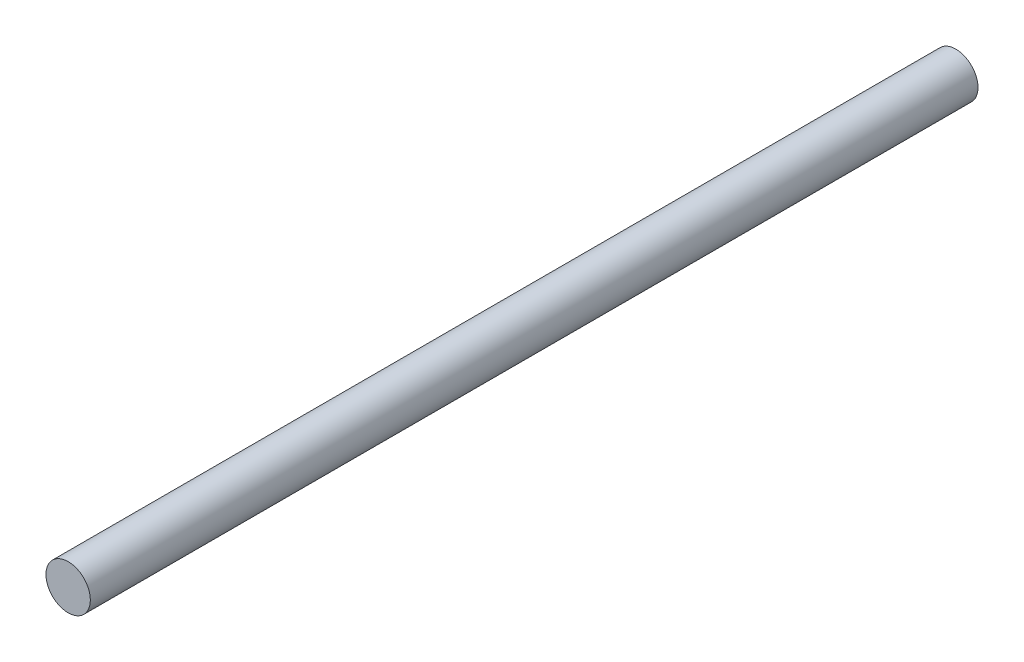
SolidWorks part; units mm, degrees
material "Alliage 1060"
ref_plane "Plan de dessus" through (0, 0, 0) normal (0, 0, 1) x (1, 0, 0)
ref_plane "Plan de droite" through (0, 0, 0) normal (0, 1, 0) x (1, 0, 0)
ref_plane "Plan de face" through (0, 0, 0) normal (1, 0, 0) x (0, 0, -1)
sketch "Esquisse1" plane through (0, 0, 0) normal (0, 0, 1) x (1, 0, 0)
  circle A0 centre (0, 0) radius 50
  dimension "D1" = 100
extrude "Boss.-Extru.1" add sketch "Esquisse1" along normal blind 2000
